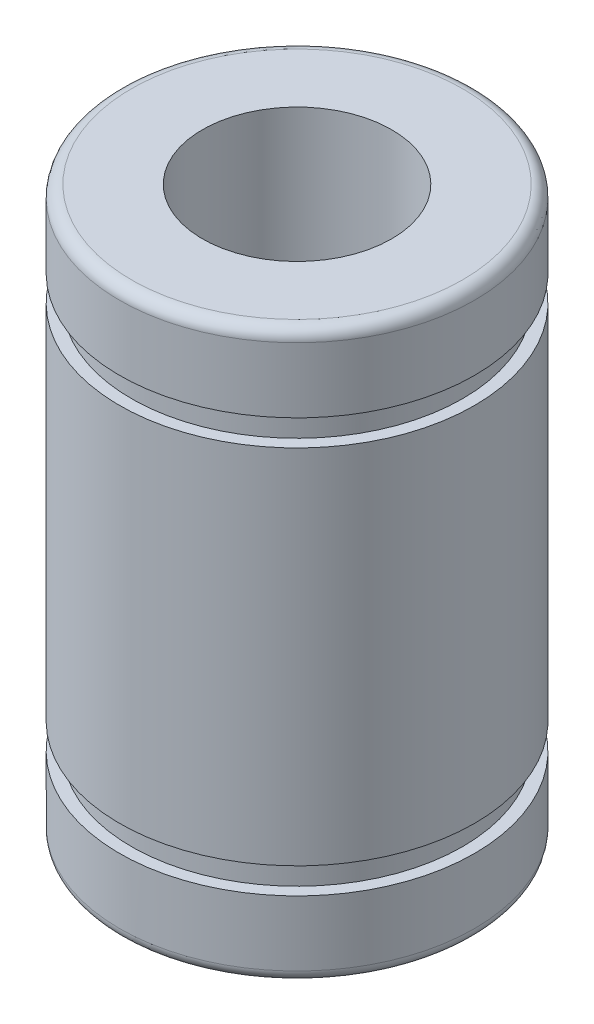
SolidWorks part; units mm, degrees
ref_plane "Front Plane" through (0, 0, 0) normal (0, 0, 1) x (1, 0, 0)
ref_plane "Top Plane" through (0, 0, 0) normal (0, 1, 0) x (1, 0, 0)
ref_plane "Right Plane" through (0, 0, 0) normal (1, 0, 0) x (0, 0, -1)
sketch "Sketch1" plane through (0, 0, 0) normal (0, 0, 1) x (1, 0, 0)
  line L0 (-4, 0) -> (0, 0) construction
  line L1 (0, 0) -> (0, 12) construction
  line L2 (-4, 12) -> (-7.5, 12)
  line L3 (-7.5, 12) -> (-7.5, 8.75)
  line L4 (-7.5, 8.75) -> (-7, 8.75)
  line L5 (-7, 8.75) -> (-7, 7.65)
  line L6 (-7, 7.65) -> (-7.5, 7.65)
  line L7 (-7.5, 7.65) -> (-7.5, -7.65)
  line L8 (-4, 12) -> (-4, -12)
  line L10 (-7, -7.65) -> (-7.5, -7.65)
  line L11 (-7, -8.75) -> (-7, -7.65)
  line L12 (-7.5, -8.75) -> (-7, -8.75)
  line L13 (-7.5, -12) -> (-7.5, -8.75)
  line L14 (-4, -12) -> (-7.5, -12)
  dimension "D2" = 1.1
  dimension "D3" = 3.25
  dimension "D4" = 4
  dimension "D5" = 7.5
  dimension "D6" = 7
revolve "Revolve1" add sketch "Sketch1" angle 360 about L1
fillet "Fillet1" radius 0.5 2 edges at (7.5, -12, 0) (7.5, 12, 0)
